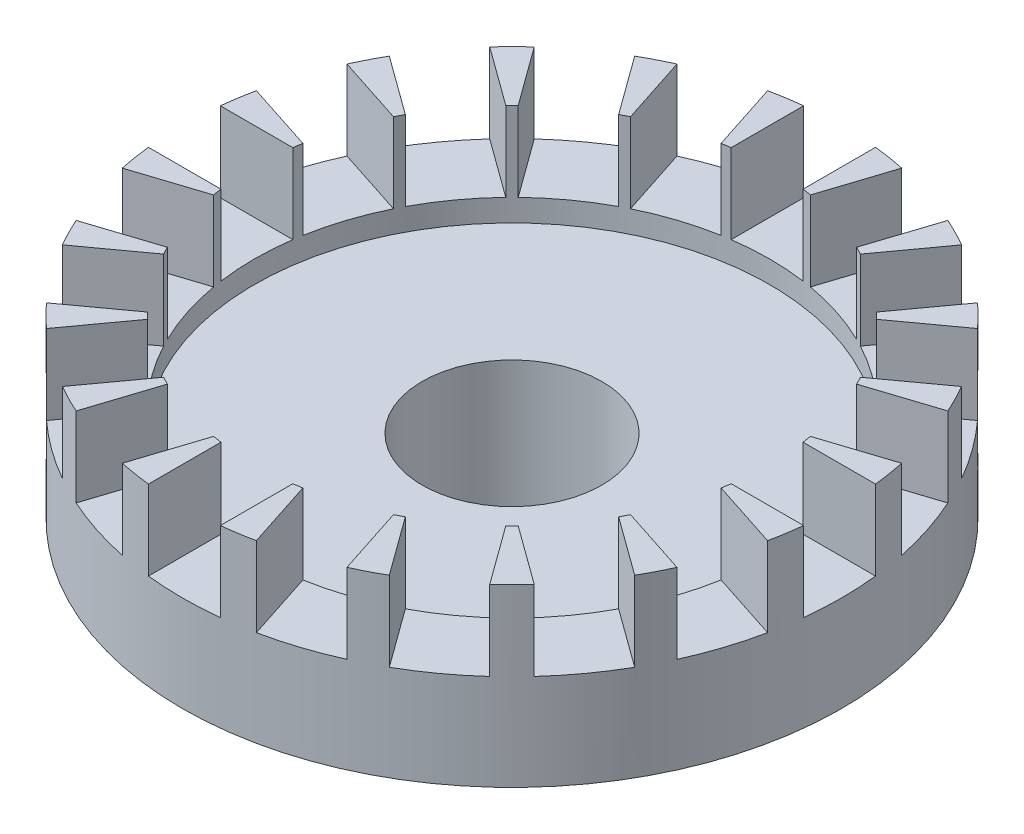
SolidWorks part; units mm, degrees
other "标注1"
sketch "草图3" plane through (-22.25, 4, -10) normal (-0.231, 0.6469, -0.7268) x (-0.9696, -0.2151, 0.1167)
ref_plane "前视基准面" through (0, 0, 0) normal (0, 0, 1) x (1, 0, 0)
ref_plane "上视基准面" through (0, 0, 0) normal (0, 1, 0) x (1, 0, 0)
ref_plane "右视基准面" through (0, 0, 0) normal (1, 0, 0) x (0, 0, -1)
other "Configuration Table"
sketch "草图4" plane through (0, 0, 0) normal (0, 1, 0) x (1, 0, 0)
  circle A0 centre (0, 0) radius 5.5
  circle A1 centre (0, 0) radius 1.5
  dimension "D1" = 11
  dimension "D2" = 3
extrude "凸台-拉伸1" add sketch "草图4" along normal blind 2.93 contours A0 | A1
sketch "草图5" plane through (0, 0, 0) normal (0, -1, 0) x (1, 0, 0)
  circle A0 centre (0, 0) radius 2.5
  circle A1 centre (0, 0) radius 1.5
  circle A2 centre (0, 0) radius 1.5 construction
  dimension "D1" = 5
extrude "凸台-拉伸2" add sketch "草图5" along normal blind 2
sketch "草图6" plane through (0, 2.93, 0) normal (0, 1, 0) x (1, 0, 0)
  circle A0 centre (0, 0) radius 4.3
  circle A1 centre (0, 0) radius 5.5 construction
  dimension "D1" = 1.2
extrude "切除-拉伸1" cut sketch "草图6" against normal blind 1.7
sketch "草图7" plane through (0, 2.93, 0) normal (0, 1, 0) x (1, 0, 0)
  line L0 (-0.6, 5.5) -> (-0.6, 4.2579)
  line L1 (-0.6, 5.5) -> (0.6, 5.5)
  line L2 (-0.6, 4.2579) -> (0.6, 4.2579)
  line L3 (0.6, 5.5) -> (0.6, 4.2579)
  line L4 (0, 5.5) -> (0, 4.2579)
  circle A2 centre (0, 0) radius 5.5 construction
  circle A3 centre (0, 0) radius 4.3 construction
  dimension "D1" = 1.2
extrude "切除-拉伸2" cut sketch "草图7" against normal offset from surface (1.33 mm away) 1.6 contours L3 L2 L0 L1 up to face at (0, 0, 5.5)
pattern_circular "阵列(圆周)1" count 20 over 360 about axis through (0, 0, 0) along (0, 1, 0) of "切除-拉伸2"
